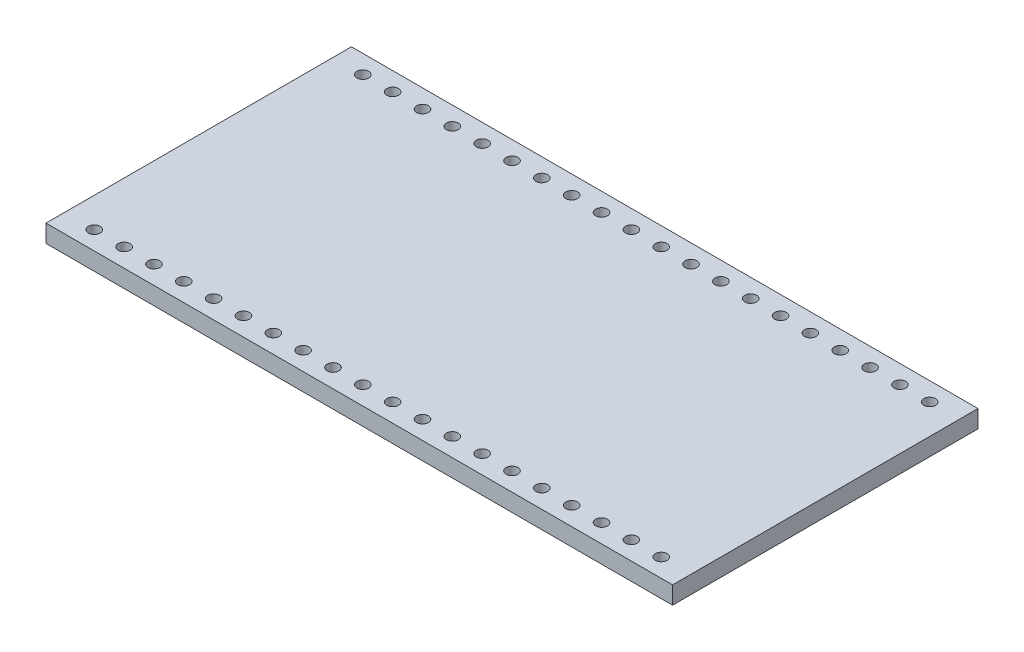
SolidWorks part; units mm, degrees
ref_plane "Front Plane" through (0, 0, 0) normal (0, 0, 1) x (1, 0, 0)
ref_plane "Top Plane" through (0, 0, 0) normal (0, 1, 0) x (1, 0, 0)
ref_plane "Right Plane" through (0, 0, 0) normal (1, 0, 0) x (0, 0, -1)
sketch "Sketch1" plane through (0, 0, 0) normal (0, 1, 0) x (1, 0, 0)
  line L1 (0, 0) -> (53.34, 0)
  line L2 (0, 0) -> (0, 26)
  line L3 (0, 26) -> (53.34, 26)
  line L4 (53.34, 0) -> (53.34, 26)
  dimension "D1" = 26
  dimension "D2" = 53.34
extrude "Boss-Extrude1" add sketch "Sketch1" along normal blind 1.5
sketch "Sketch2" plane through (0, 1.5, 0) normal (0, 1, 0) x (1, 0, 0)
  line L0 (0, 26) -> (0, 0) construction
  line L1 (0, 0) -> (53.34, 0) construction
  circle A0 centre (2.54, 1.57) radius 0.5
  circle A1 centre (2.54, 24.43) radius 0.5
  dimension "D4" = 1
  dimension "D1" = 22.86
  dimension "D2" = 2.54
  dimension "D3" = 1.57
extrude "Cut-Extrude1" cut sketch "Sketch2" against normal up to next
pattern_linear "LPattern1" count 20 spacing 2.54 along (1, 0, 0) of "Cut-Extrude1"
